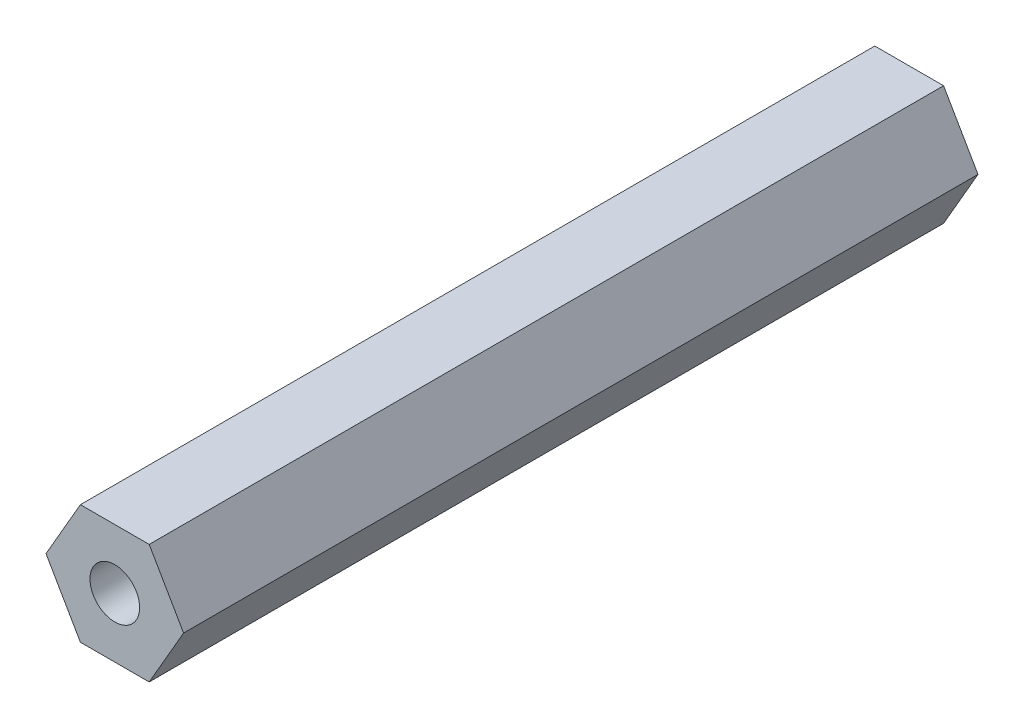
SolidWorks part; units mm, degrees
ref_plane "Front Plane" through (0, 0, 0) normal (0, 0, 1) x (1, 0, 0)
ref_plane "Top Plane" through (0, 0, 0) normal (0, 1, 0) x (1, 0, 0)
ref_plane "Right Plane" through (0, 0, 0) normal (1, 0, 0) x (0, 0, -1)
sketch "Sketch1" plane through (0, 0, 0) normal (0, 0, 1) x (1, 0, 0)
  line L1 (3.4641, 0) -> (1.7321, 3)
  line L2 (1.7321, 3) -> (-1.7321, 3)
  line L3 (-1.7321, 3) -> (-3.4641, 0)
  line L4 (-3.4641, 0) -> (-1.7321, -3)
  line L5 (-1.7321, -3) -> (1.7321, -3)
  line L6 (1.7321, -3) -> (3.4641, 0)
  circle A0 centre (0, 0) radius 3 construction
extrude "Boss-Extrude1" add sketch "Sketch1" against normal blind 40
sketch "Sketch2" plane through (0, 0, 0) normal (0, 0, 1) x (1, 0, 0)
  circle A0 centre (0, 0) radius 1.25
extrude "Cut-Extrude1" cut sketch "Sketch2" against normal through all
